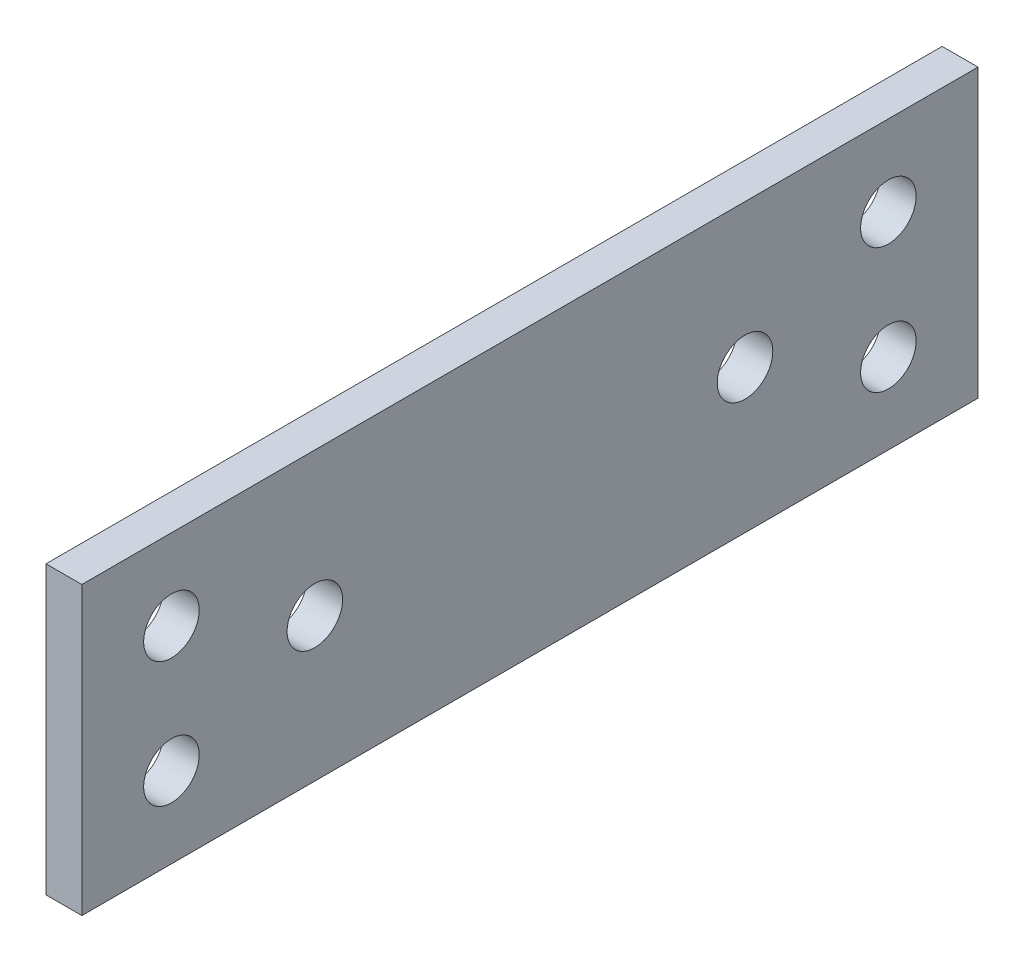
SolidWorks part; units mm, degrees
material "Thornel Mat VMA"
ref_plane "前视基准面" through (0, 0, 0) normal (0, 0, 1) x (1, 0, 0)
ref_plane "上视基准面" through (0, 0, 0) normal (0, 1, 0) x (1, 0, 0)
ref_plane "右视基准面" through (0, 0, 0) normal (1, 0, 0) x (0, 0, -1)
sketch "草图1" plane through (0, 0, 0) normal (1, 0, 0) x (0, 0, -1)
  line L0 (0, 0) -> (9.198, 0) construction
  line L1 (25, -8) -> (-25, -8)
  line L2 (25, -8) -> (25, 8)
  line L3 (25, 8) -> (-25, 8)
  line L4 (-25, -8) -> (-25, 8)
  line L5 (25, -8) -> (-25, 8) construction
  line L6 (25, 8) -> (-25, -8) construction
  line L7 (0, 0) -> (0, 7.0347) construction
  circle A0 centre (-12, 0) radius 1.55
  circle A1 centre (-20, 3.5) radius 1.55
  circle A2 centre (-20, -3.5) radius 1.55
  circle A3 centre (20, 3.5) radius 1.55
  circle A4 centre (20, -3.5) radius 1.55
  circle A5 centre (12, 0) radius 1.55
  point P0 (0, 0)
  dimension "D3" = 3.1
  dimension "D9" = 5
  dimension "D1" = 16
  dimension "D2" = 5
  dimension "D4" = 7
  dimension "D5" = 8
  dimension "D6" = 50
  dimension "D7" = 7
  dimension "D8" = 8
extrude "凸台-拉伸1" add sketch "草图1" along normal blind 2
